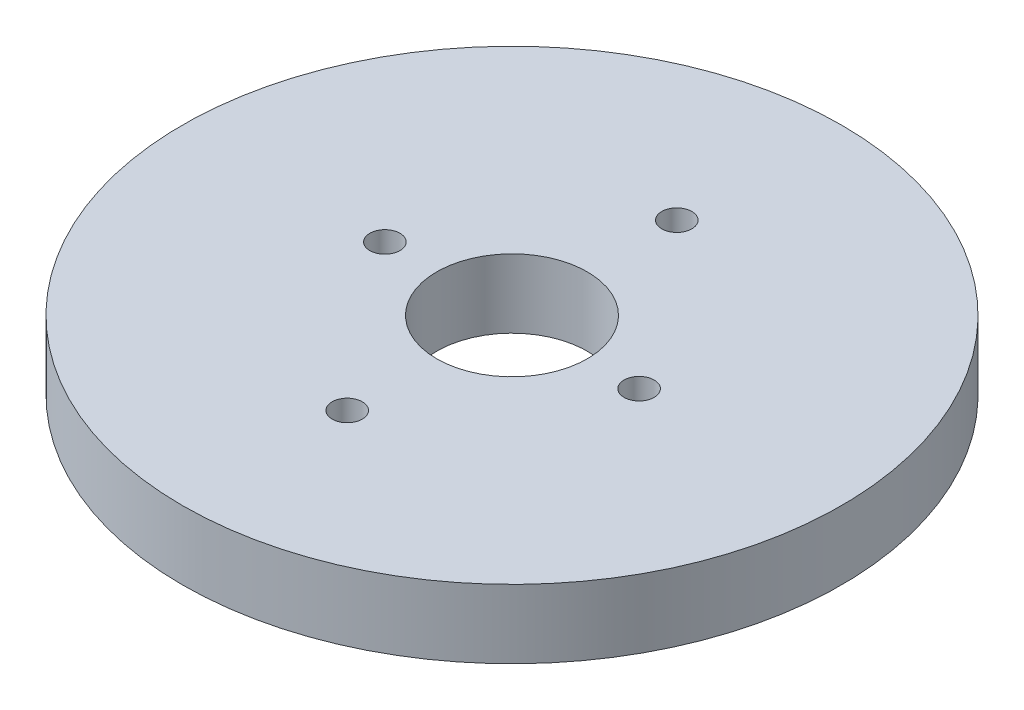
SolidWorks part; units mm, degrees
ref_plane "Front Plane" through (0, 0, 0) normal (0, 0, 1) x (1, 0, 0)
ref_plane "Top Plane" through (0, 0, 0) normal (0, 1, 0) x (1, 0, 0)
ref_plane "Right Plane" through (0, 0, 0) normal (1, 0, 0) x (0, 0, -1)
sketch "Sketch1" plane through (0, 0, 0) normal (0, 1, 0) x (1, 0, 0)
  line L0 (0, 0) -> (-6.75, 0) construction
  line L1 (0, 0) -> (0, -8.75) construction
  circle A0 centre (0, 0) radius 4
  circle A1 centre (0, 0) radius 17.5
  circle A2 centre (-6.75, 0) radius 0.8
  circle A3 centre (0, -8.75) radius 0.8
  circle A4 centre (6.75, 0) radius 0.8
  circle A5 centre (0, 8.75) radius 0.8
  point P15 (0, 0)
  dimension "D1" = 8
  dimension "D2" = 35
  dimension "D5" = 1.6
  dimension "D3" = 6.75
  dimension "D4" = 8.75
  dimension "D6" = 2
extrude "Boss-Extrude1" add sketch "Sketch1" along normal blind 3.65
